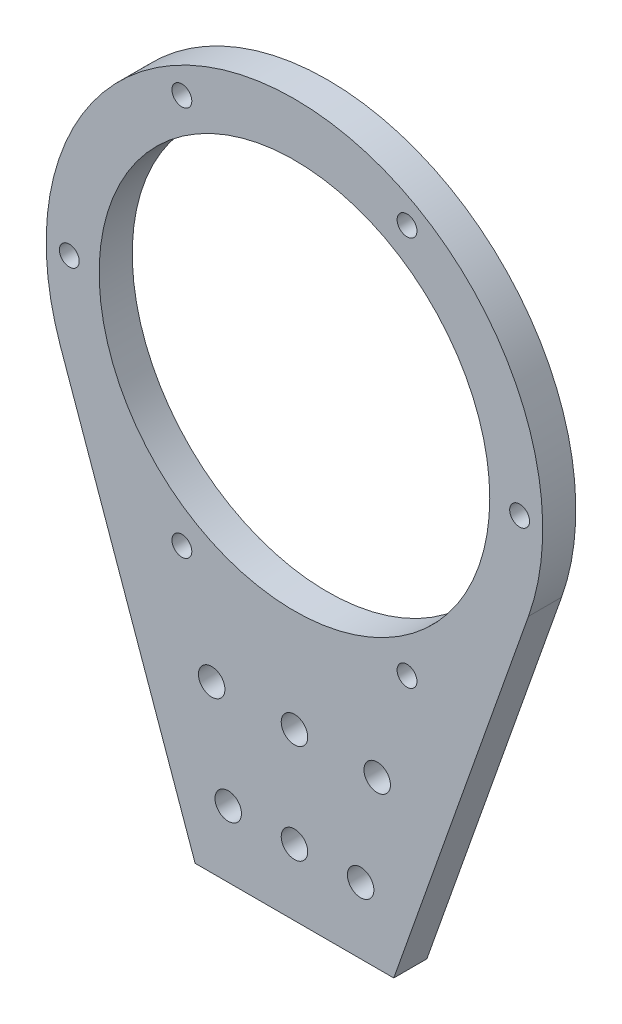
SolidWorks part; units mm, degrees
material "Acrylic (Medium-high impact)"
ref_plane "Front Plane" through (0, 0, 0) normal (0, 0, 1) x (1, 0, 0)
ref_plane "Top Plane" through (0, 0, 0) normal (0, 1, 0) x (1, 0, 0)
ref_plane "Right Plane" through (0, 0, 0) normal (1, 0, 0) x (0, 0, -1)
sketch "Sketch1" plane through (0, 0, 0) normal (0, 0, 1) x (1, 0, 0)
  line L0 (0, 0) -> (0, -75.7544) construction
  line L1 (-15, -70) -> (15, -70)
  line L4 (15, -70) -> (35.3503, -12.5142)
  line L5 (-15, -70) -> (-35.3503, -12.5142)
  circle A0 centre (0, 0) radius 29.5
  circle A1 centre (0, 0) radius 37.5
  arc A2 (-22.5, -30) -> (6.0194, -37.0137) centre (0, 0) ccw
  arc A3 (37.5, 0) -> (6.0194, -37.0137) centre (0, 0) cw
  arc A4 (-35.3503, -12.5142) -> (-22.5, -30) centre (0, 0) ccw
  arc A5 (6.0194, -37.0137) -> (-5.2342, -37.1329) centre (0, 0) ccw
  arc A6 (-22.5, -30) -> (-35.3503, -12.5142) centre (0, 0) cw
  arc A7 (6.0194, -37.0137) -> (-5.2342, -37.1329) centre (0, 0) ccw
  arc A8 (35.3503, -12.5142) -> (-35.3503, -12.5142) centre (0, 0) cw
  dimension "D1" = 30
  dimension "D2" = 75
  dimension "D3" = 59
  dimension "D4" = 70
  dimension "D5" = 15
extrude "Boss-Extrude1" add sketch "Sketch1" along normal blind 5
sketch "Sketch12" plane through (0, 0, 0) normal (0, 0, -1) x (-1, 0, 0)
  line L0 (15, -70) -> (-15, -70) construction
  line L3 (0, 53.5172) -> (0, -108.1009) construction
  circle A0 centre (-12.5, -45) radius 2
  circle A2 centre (12.5, -45) radius 2
  circle A3 centre (-10, -60) radius 2
  circle A5 centre (10, -60) radius 2
  circle A6 centre (0, -45) radius 2
  circle A7 centre (0, -60) radius 2
  dimension "D2" = 10
  dimension "D6" = 12.5
  dimension "D9" = 25
  dimension "D3" = 25
  dimension "D4" = 10
  dimension "D5" = 25
  dimension "D7" = 10
  dimension "D8" = 10
  dimension "D10" = 12.5
  dimension "D11" = 10
extrude "Cut-Extrude8" cut sketch "Sketch12" against normal blind 7
sketch "Sketch9" plane through (0, 0, 5) normal (0, 0, 1) x (1, 0, 0)
  line L0 (60.1553, 0) -> (-60.1553, 0) construction
  line L1 (-60.1553, 0) -> (0, 0) construction
  line L2 (0, 0) -> (27.4803, 47.5973) construction
  line L3 (27.4803, 47.5973) -> (-28.626, -49.5817) construction
  line L4 (-28.626, -49.5817) -> (0, 0) construction
  line L5 (-29.2217, 50.6135) -> (0, 0) construction
  line L6 (0, 0) -> (29.2328, -50.6327) construction
  circle A0 centre (0, 0) radius 34.01 construction
  circle A1 centre (17.005, 29.4535) radius 1.5
  circle A2 centre (34.01, 0) radius 1.5
  circle A3 centre (17.005, -29.4535) radius 1.5
  circle A4 centre (-17.005, -29.4535) radius 1.5
  circle A5 centre (-34.01, 0) radius 1.5
  circle A6 centre (-17.005, 29.4535) radius 1.5
  dimension "D1" = 60
  dimension "D2" = 60
extrude "Cut-Extrude5" cut sketch "Sketch9" against normal blind 7
